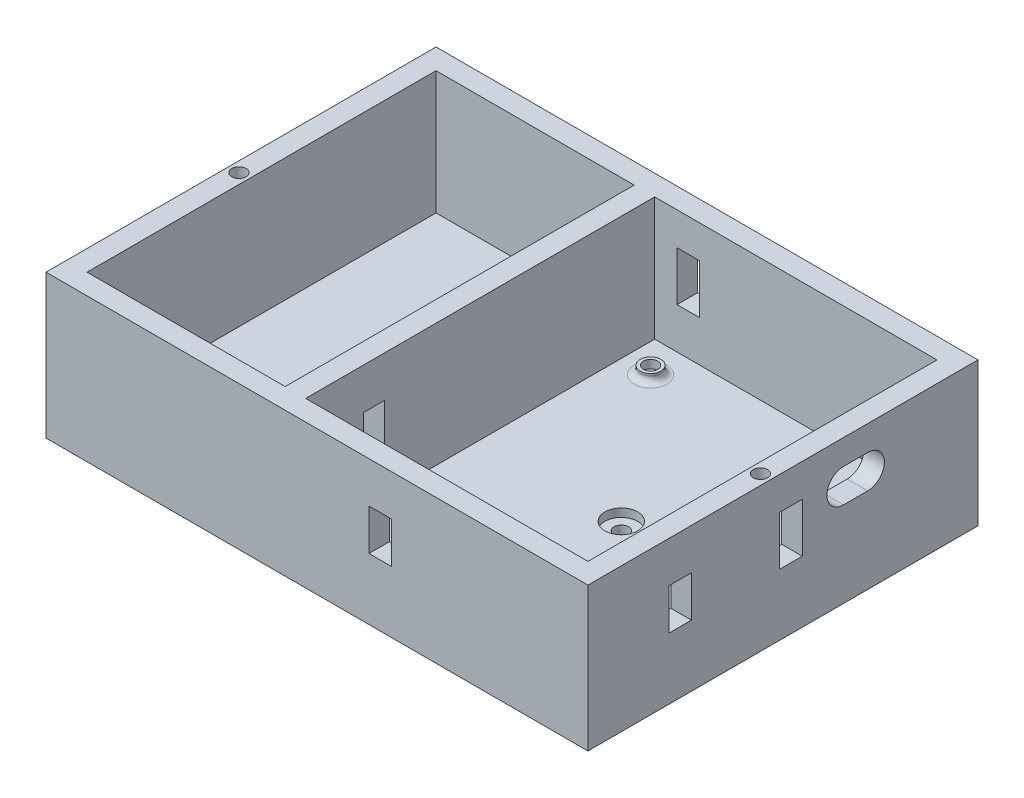
SolidWorks part; units mm, degrees
ref_plane "Front Plane" through (0, 0, 0) normal (0, 0, 1) x (1, 0, 0)
ref_plane "Top Plane" through (0, 0, 0) normal (0, 1, 0) x (1, 0, 0)
ref_plane "Right Plane" through (0, 0, 0) normal (1, 0, 0) x (0, 0, -1)
sketch "Sketch1" plane through (0, 0, 0) normal (0, 1, 0) x (1, 0, 0)
  line L1 (-66, 47.5) -> (66, 47.5)
  line L2 (-66, 47.5) -> (-66, -47.5)
  line L3 (-66, -47.5) -> (66, -47.5)
  line L4 (66, 47.5) -> (66, -47.5)
  line L5 (-66, 47.5) -> (66, -47.5) construction
  line L6 (-66, -47.5) -> (66, 47.5) construction
  point P4 (0, 0)
  dimension "D1" = 95
  dimension "D2" = 132
extrude "Boss-Extrude1" add sketch "Sketch1" along normal blind 35
sketch "Sketch2" plane through (0, 35, 0) normal (0, 1, 0) x (1, 0, 0)
  line L1 (61, -42.5) -> (-61, -42.5)
  line L2 (61, -42.5) -> (61, 42.5)
  line L3 (61, 42.5) -> (-61, 42.5)
  line L4 (-61, -42.5) -> (-61, 42.5)
  line L5 (61, -42.5) -> (-61, 42.5) construction
  line L6 (61, 42.5) -> (-61, -42.5) construction
  line L7 (-66, -47.5) -> (66, -47.5) construction
  line L8 (66, 47.5) -> (-66, 47.5) construction
  point P4 (0, 0)
  dimension "D1" = 122
  dimension "D2" = 5
  dimension "D3" = 5
extrude "Cut-Extrude1" cut sketch "Sketch2" against normal blind 30
sketch "Sketch4" plane through (0, 5, 0) normal (0, 1, 0) x (1, 0, 0)
  line L0 (-61, -42.5) -> (61, -42.5) construction
  line L1 (57.5, -40) -> (-6.5, -40) construction
  line L2 (57.5, -40) -> (57.5, 40) construction
  line L3 (57.5, 40) -> (-6.5, 40) construction
  line L4 (-6.5, -40) -> (-6.5, 40) construction
  line L5 (57.5, -40) -> (-6.5, 40) construction
  line L6 (57.5, 40) -> (-6.5, -40) construction
  line L7 (61, -42.5) -> (61, 42.5) construction
  line L8 (61, 42.5) -> (-61, 42.5) construction
  line L9 (-7.75, -42.5) -> (-12.75, -42.5)
  line L10 (-7.75, -42.5) -> (-7.75, 42.5)
  line L11 (-7.75, 42.5) -> (-12.75, 42.5)
  line L12 (-12.75, -42.5) -> (-12.75, 42.5)
  line L13 (-7.75, -42.5) -> (-12.75, 42.5) construction
  line L14 (-7.75, 42.5) -> (-12.75, -42.5) construction
  line L15 (-61, 42.5) -> (-61, -42.5) construction
  line L16 (-17, -40) -> (-57.5, -40) construction
  line L17 (-17, -40) -> (-17, 40) construction
  line L18 (-17, 40) -> (-57.5, 40) construction
  line L19 (-57.5, -40) -> (-57.5, 40) construction
  line L20 (-17, -40) -> (-57.5, 40) construction
  line L21 (-17, 40) -> (-57.5, -40) construction
  line L22 (-61, -42.5) -> (61, -42.5) construction
  point P4 (25.5, 0)
  point P13 (-10.25, 0)
  point P20 (-37.25, 0)
  dimension "D1" = 64
  dimension "D2" = 80
  dimension "D3" = 2.5
  dimension "D4" = 3.5
  dimension "D5" = 4.25
  dimension "D6" = 5
  dimension "D7" = 40.5
  dimension "D8" = 80
  dimension "D9" = 3.5
  dimension "D10" = 2.5
  dimension "D11" = 1.25
extrude "Boss-Extrude2" add sketch "Sketch4" along normal through all
sketch "Sketch5" plane through (0, 5, 0) normal (0, 1, 0) x (1, 0, 0)
  line L0 (-7.75, -42.5) -> (61, -42.5) construction
  line L1 (59.55, -39) -> (-4.75, -39) construction
  line L2 (59.55, -39) -> (59.55, 39) construction
  line L3 (59.55, 39) -> (-4.75, 39) construction
  line L4 (-4.75, -39) -> (-4.75, 39) construction
  line L5 (59.55, -39) -> (-4.75, 39) construction
  line L6 (59.55, 39) -> (-4.75, -39) construction
  line L8 (-7.75, -42.5) -> (-7.75, 42.5) construction
  circle A0 centre (55.55, -35.5) radius 1.75
  circle A1 centre (-0.75, -35.5) radius 1.75
  circle A2 centre (-0.75, 34.5) radius 1.75
  circle A3 centre (55.25, 34.4994) radius 1.75
  circle A4 centre (55.55, -35.5) radius 2.5
  circle A5 centre (-0.75, -35.5) radius 2.5
  circle A6 centre (55.25, 34.4994) radius 2.5
  circle A7 centre (-0.75, 34.5) radius 2.5
  point P4 (27.4, 0)
  dimension "D5" = 3.5
  dimension "D6" = 3.5
  dimension "D8" = 4
  dimension "D9" = 3.5
  dimension "D10" = 3.5
  dimension "D14" = 5
  dimension "D15" = 5
  dimension "D16" = 5
  dimension "D17" = 5
  dimension "D1" = 64.3
  dimension "D2" = 78
  dimension "D3" = 3.5
  dimension "D4" = 3
  dimension "D7" = 56.3
  dimension "D11" = 56
  dimension "D12" = 70
  dimension "D18" = 70
  dimension "D19" = 3.5
  dimension "D20" = 4
extrude "Boss-Extrude3" add sketch "Sketch5" along normal blind 2
fillet "Fillet1" radius 1.5 4 edges at (55.25, 5, -31.9994) (-0.75, 5, -32) (55.55, 5, 38) (-0.75, 5, 38)
sketch "Sketch6" plane through (0, 5, 0) normal (0, 1, 0) x (1, 0, 0)
  line L0 (-7.75, -42.5) -> (61, -42.5) construction
  line L1 (60.25, -40) -> (-5.25, -40) construction
  line L2 (60.25, -40) -> (60.25, 40) construction
  line L3 (60.25, 40) -> (-5.25, 40) construction
  line L4 (-5.25, -40) -> (-5.25, 40) construction
  line L5 (60.25, -40) -> (-5.25, 40) construction
  line L6 (60.25, 40) -> (-5.25, -40) construction
  line L8 (-7.75, -42.5) -> (-7.75, 42.5) construction
  line L10 (9.9949, -28) -> (-1.75, -28) construction
  line L11 (9.9949, -28) -> (9.9949, -17.4471) construction
  line L12 (9.9949, -17.4471) -> (-1.75, -17.4471) construction
  line L13 (-1.75, -28) -> (-1.75, -17.4471) construction
  line L14 (9.9949, -28) -> (-1.75, -17.4471) construction
  line L15 (9.9949, -17.4471) -> (-1.75, -28) construction
  point P4 (27.5, 0)
  point P13 (4.1225, -22.7235)
  dimension "D1" = 65.5
  dimension "D2" = 80
  dimension "D3" = 2.5
  dimension "D4" = 2.5
  dimension "D5" = 12
  dimension "D6" = 3.5
sketch "Sketch7" plane through (-7.75, 0, 0) normal (1, 0, 0) x (0, 0, -1)
  line L0 (-42.5, 20) -> (42.5, 20) construction
  line L5 (-42.5, 35) -> (-42.5, 5) construction
  line L6 (-28.3633, 25) -> (-23.3633, 25)
  line L7 (42.5, 35) -> (42.5, 5) construction
  line L9 (-28.3633, 25) -> (-28.3633, 15)
  line L10 (-28.3633, 15) -> (-23.3633, 15)
  line L11 (-23.3633, 25) -> (-23.3633, 15)
  line L12 (-28.3633, 25) -> (-23.3633, 15) construction
  line L13 (-28.3633, 15) -> (-23.3633, 25) construction
  point P10 (-25.8633, 20)
  dimension "D1" = 5
  dimension "D3" = 10
extrude "Cut-Extrude3" cut sketch "Sketch7" against normal blind 10
sketch "Sketch8" plane through (0, 5, 0) normal (0, 1, 0) x (1, 0, 0)
  line L3 (61, 0) -> (-7.75, 0) construction
  line L4 (61, -42.5) -> (61, 42.5) construction
  line L5 (-7.75, -42.5) -> (-7.75, 42.5) construction
  line L6 (-36.875, -42.5) -> (-36.875, 42.5) construction
  line L7 (-61, -42.5) -> (-12.75, -42.5) construction
  line L8 (-12.75, 42.5) -> (-61, 42.5) construction
  line L9 (-12.75, 0) -> (-61, 0) construction
  line L10 (-12.75, 42.5) -> (-12.75, -42.5) construction
  line L11 (-61, 42.5) -> (-61, -42.5) construction
  circle A0 centre (26.625, 0) radius 1.75
  circle A1 centre (-36.875, 0) radius 1.7
  point P30 (-36.875, 0)
  dimension "D1" = 3.5
  dimension "D2" = 3.4
extrude "Cut-Extrude4" cut sketch "Sketch8" against normal blind 10
sketch "Sketch9" plane through (0, 5, 0) normal (0, 1, 0) x (1, 0, 0)
  circle A0 centre (26.625, 0) radius 4
  circle A1 centre (-36.875, 0) radius 4
  dimension "D1" = 8
  dimension "D2" = 8
extrude "Cut-Extrude6" cut sketch "Sketch9" against normal blind 2
sketch "Sketch11" plane through (61, 0, 0) normal (-1, 0, 0) x (0, 0, 1)
  line L0 (38, 7) -> (33, 7) construction
  line L1 (-40, 32) -> (40, 32) construction
  line L2 (-40, 32) -> (-40, 7) construction
  line L3 (-40, 7) -> (40, 7) construction
  line L4 (40, 32) -> (40, 7) construction
  line L5 (0, 7) -> (0, 32) construction
  line L6 (-40, 19.5) -> (40, 19.5) construction
  line L7 (-42.5, 5) -> (-42.5, 35) construction
  line L8 (-14.75, 24.85) -> (-20.65, 24.85) construction
  line L9 (-4.7, 27) -> (0.8, 27)
  line L10 (-4.7, 27) -> (-4.7, 15)
  line L11 (-4.7, 15) -> (0.8, 15)
  line L12 (0.8, 27) -> (0.8, 15)
  line L13 (-1.95, 15) -> (-1.95, 27) construction
  line L14 (-4.7, 21) -> (0.8, 21) construction
  line L15 (22.3, 25) -> (27.8, 25)
  line L16 (22.3, 25) -> (22.3, 15)
  line L17 (22.3, 15) -> (27.8, 15)
  line L18 (27.8, 25) -> (27.8, 15)
  line L19 (25.05, 15) -> (25.05, 25) construction
  line L20 (22.3, 20) -> (27.8, 20) construction
  line L25 (-14.75, 20.8) -> (-20.65, 20.8)
  line L26 (-14.75, 28.9) -> (-20.65, 28.9)
  line L29 (42.5, 5) -> (-42.5, 5) construction
  line L31 (-10.7, 24.85) -> (-24.7, 24.85) construction
  arc A2 (-14.75, 20.8) -> (-14.75, 28.9) centre (-14.75, 24.85) ccw
  arc A3 (-20.65, 28.9) -> (-20.65, 20.8) centre (-20.65, 24.85) ccw
  point P18 (-17.7, 24.85)
  point P88 (-1.95, 21)
  point P93 (25.05, 20)
  point P184 (0, 19.5)
  dimension "D11" = 8.1
  dimension "D1" = 80
  dimension "D2" = 2.5
  dimension "D3" = 25
  dimension "D4" = 35.3
  dimension "D5" = 13.8
  dimension "D6" = 5.5
  dimension "D7" = 12
  dimension "D8" = 10
  dimension "D9" = 12.2
  dimension "D10" = 13
  dimension "D12" = 14
  dimension "D13" = 8
  dimension "D14" = 2
extrude "Cut-Extrude7" cut sketch "Sketch11" against normal blind 10
sketch "Sketch13" plane through (0, 0, 42.5) normal (0, 0, -1) x (-1, 0, 0)
  line L0 (3.25, 7) -> (-1.75, 7) construction
  line L1 (-58.77, 32) -> (5.53, 32) construction
  line L2 (-58.77, 32) -> (-58.77, 7) construction
  line L3 (-58.77, 7) -> (5.53, 7) construction
  line L4 (5.53, 32) -> (5.53, 7) construction
  line L5 (-26.62, 7) -> (-26.62, 32) construction
  line L6 (-58.77, 19.5) -> (5.53, 19.5) construction
  line L7 (-61, 5) -> (-61, 35) construction
  line L8 (7.75, 35) -> (7.75, 5) construction
  line L10 (-18.17, 25) -> (-12.67, 25)
  line L11 (-18.17, 25) -> (-18.17, 15)
  line L12 (-18.17, 15) -> (-12.67, 15)
  line L13 (-12.67, 25) -> (-12.67, 15)
  line L14 (-15.42, 15) -> (-15.42, 25) construction
  line L15 (-18.17, 20) -> (-12.67, 20) construction
  point P86 (-15.42, 20)
  point P284 (-26.62, 19.5)
  dimension "D1" = 64.3
  dimension "D2" = 25
  dimension "D3" = 2.23
  dimension "D4" = 2.22
  dimension "D5" = 18.2
  dimension "D6" = 8
  dimension "D7" = 5.5
  dimension "D8" = 10
extrude "Cut-Extrude8" cut sketch "Sketch13" against normal blind 10
sketch "Sketch14" plane through (0, 0, -42.5) normal (0, 0, 1) x (1, 0, 0)
  line L0 (-7.75, 35) -> (-7.75, 5) construction
  line L1 (-5.52, 32) -> (58.78, 32) construction
  line L2 (-5.52, 32) -> (-5.52, 7) construction
  line L3 (-5.52, 7) -> (58.78, 7) construction
  line L4 (58.78, 32) -> (58.78, 7) construction
  line L5 (26.63, 7) -> (26.63, 32) construction
  line L6 (-5.52, 19.5) -> (58.78, 19.5) construction
  line L7 (61, 5) -> (61, 35) construction
  line L8 (61, 5) -> (-7.75, 5) construction
  line L10 (-2.32, 27) -> (3.18, 27)
  line L11 (-2.32, 27) -> (-2.32, 15)
  line L12 (-2.32, 15) -> (3.18, 15)
  line L13 (3.18, 27) -> (3.18, 15)
  line L14 (0.43, 15) -> (0.43, 27) construction
  line L15 (-2.32, 21) -> (3.18, 21) construction
  point P140 (26.63, 19.5)
  point P199 (0.43, 21)
  dimension "D1" = 25
  dimension "D2" = 2.23
  dimension "D3" = 2.22
  dimension "D4" = 2
  dimension "D5" = 5.5
  dimension "D6" = 12
  dimension "D7" = 8
  dimension "D8" = 3.2
extrude "Cut-Extrude9" cut sketch "Sketch14" against normal blind 10
sketch "Sketch15" plane through (0, 35, 0) normal (0, 1, 0) x (1, 0, 0)
  line L0 (-61, -47.5) -> (-66, -47.5) construction
  line L2 (-63.5, -47.5) -> (-63.5, 44.5823) construction
  line L7 (-66, -47.5) -> (66, -47.5) construction
  line L9 (0, 47.5) -> (0, -47.5) construction
  line L10 (66, 47.5) -> (66, -47.5) construction
  circle A0 centre (-63.5, -3) radius 1.75
  circle A1 centre (63.5, -3) radius 1.75
  dimension "D1" = 3.5
  dimension "D2" = 44.5
extrude "Cut-Extrude10" cut sketch "Sketch15" against normal blind 10
